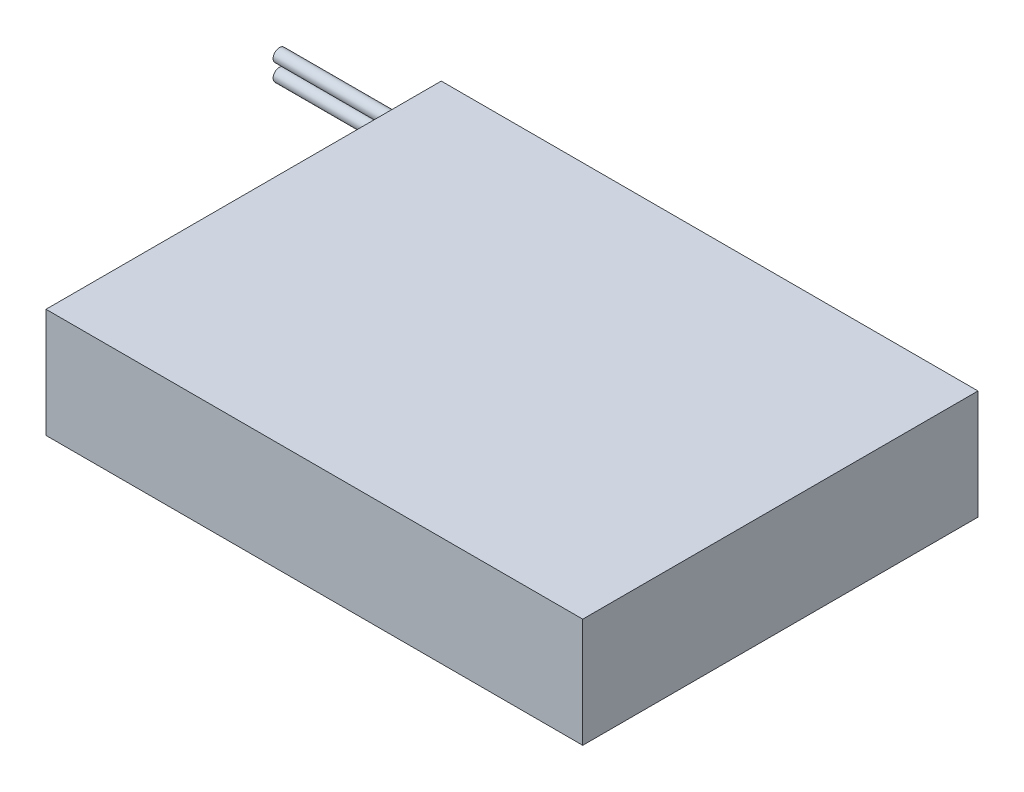
SolidWorks part; units mm, degrees
ref_plane "Plan de face" through (0, 0, 0) normal (0, 0, 1) x (1, 0, 0)
ref_plane "Plan de dessus" through (0, 0, 0) normal (0, 1, 0) x (1, 0, 0)
ref_plane "Plan de droite" through (0, 0, 0) normal (1, 0, 0) x (0, 0, -1)
sketch "Esquisse1" plane through (0, 0, 0) normal (0, 1, 0) x (1, 0, 0)
  line L1 (-35.85, 26.4) -> (35.85, 26.4)
  line L2 (-35.85, 26.4) -> (-35.85, -26.4)
  line L3 (-35.85, -26.4) -> (35.85, -26.4)
  line L4 (35.85, 26.4) -> (35.85, -26.4)
  point P4 (0, 26.4)
  point P6 (-35.85, 0)
  dimension "D1" = 71.7
  dimension "D2" = 52.8
extrude "Boss.-Extru.1" add sketch "Esquisse1" along normal mid plane 14.6
sketch "Esquisse2" plane through (-35.85, 0, 0) normal (-1, 0, 0) x (0, 0, 1)
  line L0 (0, 0) -> (5.1957, 0) construction
  circle A0 centre (-24.7877, 1.1366) radius 0.85
  circle A2 centre (-24.7877, -1.1366) radius 0.85
  point P7 (-23.6511, 1.786)
  point P8 (-24.7877, 1.1366)
  dimension "D1" = 1.7
extrude "Boss.-Extru.2" add sketch "Esquisse2" along normal blind 20
